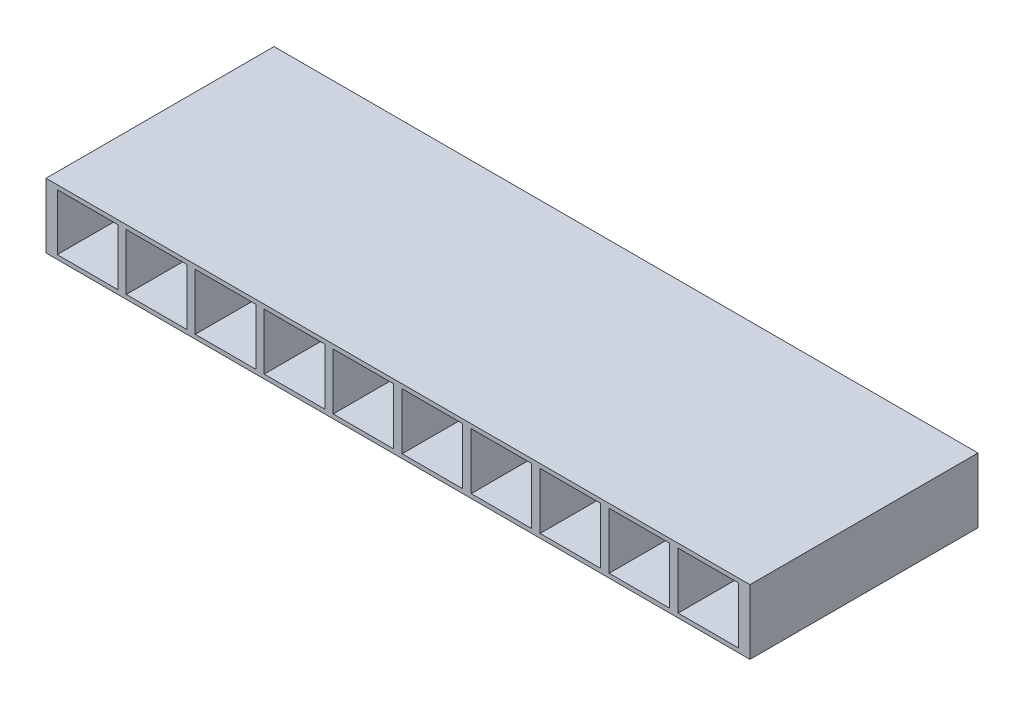
SolidWorks part; units mm, degrees
ref_plane "Plan de face" through (0, 0, 0) normal (0, 0, 1) x (1, 0, 0)
ref_plane "Plan de dessus" through (0, 0, 0) normal (0, 1, 0) x (1, 0, 0)
ref_plane "Plan de droite" through (0, 0, 0) normal (1, 0, 0) x (0, 0, -1)
sketch "Esquisse1" plane through (0, 0, 0) normal (0, 0, 1) x (1, 0, 0)
  line L0 (-9.65, -1) -> (-9.65, 1)
  line L1 (-12.5, -1.15) -> (12.5, -1.15)
  line L2 (-12.5, -1.15) -> (-12.5, 1.15)
  line L3 (-12.5, 1.15) -> (12.5, 1.15)
  line L4 (12.5, -1.15) -> (12.5, 1.15)
  line L5 (-12.5, -1.15) -> (-9.95, -0.9154) construction
  line L6 (-12.5, 1.15) -> (-9.95, 0.9154) construction
  line L7 (-12.1, -1) -> (-9.95, -1)
  line L8 (-12.1, -1) -> (-12.1, 1)
  line L9 (-12.1, 1) -> (-9.95, 1)
  line L10 (-9.95, -1) -> (-9.95, 1)
  line L11 (-12.1, -1) -> (-9.95, 1) construction
  line L12 (-12.1, 1) -> (-9.95, -1) construction
  line L13 (-7.5, -1) -> (-7.5, 1)
  line L14 (-9.65, 1) -> (-7.5, 1)
  line L15 (-9.65, -1) -> (-7.5, -1)
  line L16 (-7.2, -1) -> (-7.2, 1)
  line L17 (-5.05, -1) -> (-5.05, 1)
  line L18 (-7.2, 1) -> (-5.05, 1)
  line L19 (-7.2, -1) -> (-5.05, -1)
  line L20 (-4.75, -1) -> (-4.75, 1)
  line L21 (-2.6, -1) -> (-2.6, 1)
  line L22 (-4.75, 1) -> (-2.6, 1)
  line L23 (-4.75, -1) -> (-2.6, -1)
  line L24 (-2.3, -1) -> (-2.3, 1)
  line L25 (-0.15, -1) -> (-0.15, 1)
  line L26 (-2.3, 1) -> (-0.15, 1)
  line L27 (-2.3, -1) -> (-0.15, -1)
  line L28 (0.15, -1) -> (0.15, 1)
  line L29 (2.3, -1) -> (2.3, 1)
  line L30 (0.15, 1) -> (2.3, 1)
  line L31 (0.15, -1) -> (2.3, -1)
  line L32 (2.6, -1) -> (2.6, 1)
  line L33 (4.75, -1) -> (4.75, 1)
  line L34 (2.6, 1) -> (4.75, 1)
  line L35 (2.6, -1) -> (4.75, -1)
  line L36 (5.05, -1) -> (5.05, 1)
  line L37 (7.2, -1) -> (7.2, 1)
  line L38 (5.05, 1) -> (7.2, 1)
  line L39 (5.05, -1) -> (7.2, -1)
  line L40 (7.5, -1) -> (7.5, 1)
  line L41 (9.65, -1) -> (9.65, 1)
  line L42 (7.5, 1) -> (9.65, 1)
  line L43 (7.5, -1) -> (9.65, -1)
  line L44 (9.95, -1) -> (9.95, 1)
  line L45 (12.1, -1) -> (12.1, 1)
  line L46 (9.95, 1) -> (12.1, 1)
  line L47 (9.95, -1) -> (12.1, -1)
  point P0 (0, 0)
  point P6 (-11.025, 0)
  point P11 (0, 1.15)
  dimension "D1" = 25
  dimension "D2" = 2.3
  dimension "D3" = 2
  dimension "D4" = 2.15
  dimension "D5" = 0.4
  dimension "D7" = 0.4
  dimension "D6" = 10
extrude "Boss.-Extru.3" add sketch "Esquisse1" along normal blind 8.1
